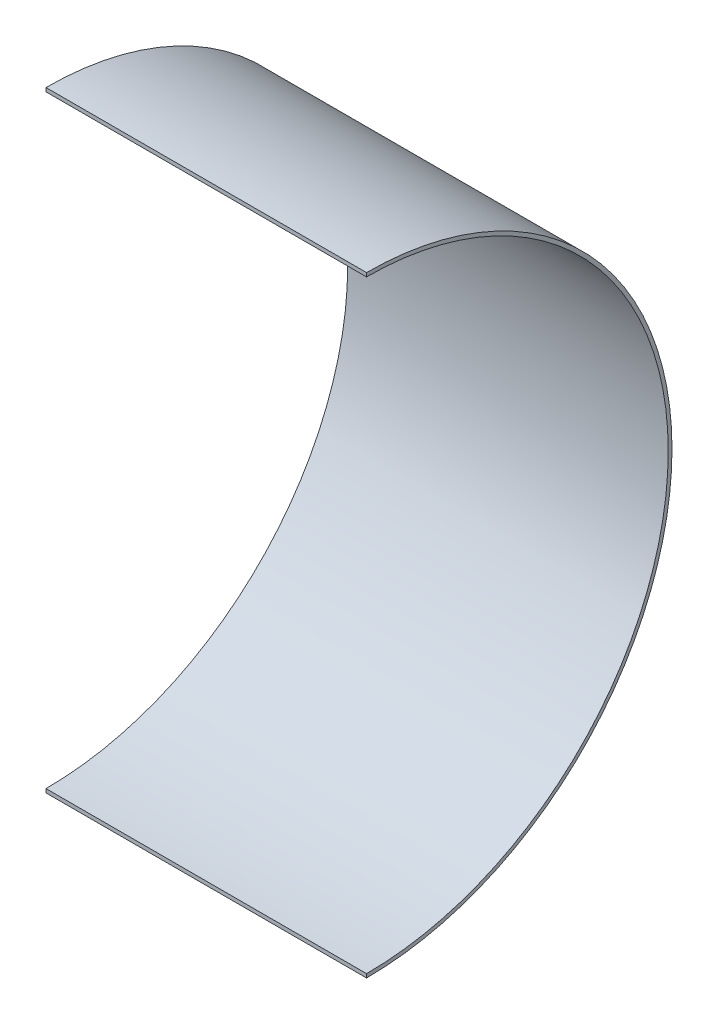
SolidWorks part; units mm, degrees
ref_plane "Front Plane" through (0, 0, 0) normal (0, 0, 1) x (1, 0, 0)
ref_plane "Top Plane" through (0, 0, 0) normal (0, 1, 0) x (1, 0, 0)
ref_plane "Right Plane" through (0, 0, 0) normal (1, 0, 0) x (0, 0, -1)
sketch "Sketch1" plane through (0, 0, 0) normal (1, 0, 0) x (0, 0, -1)
  line L0 (0, 203.2) -> (0, -203.2) construction
  line L1 (0, 203.2) -> (0, 0) construction
  line L2 (203.2, 0) -> (203.2, 203.2) construction
  line L3 (0, 203.2) -> (203.2, 203.2) construction
  line L4 (203.2, 0) -> (0, 203.2) construction
  arc A0 (0, -203.2) -> (0, 203.2) centre (0, 0) ccw
  dimension "D1" = 406.4
  dimension "D2" = 45
extrude "Extrude-Thin1" add sketch "Sketch1" along normal blind 215.9 thin
